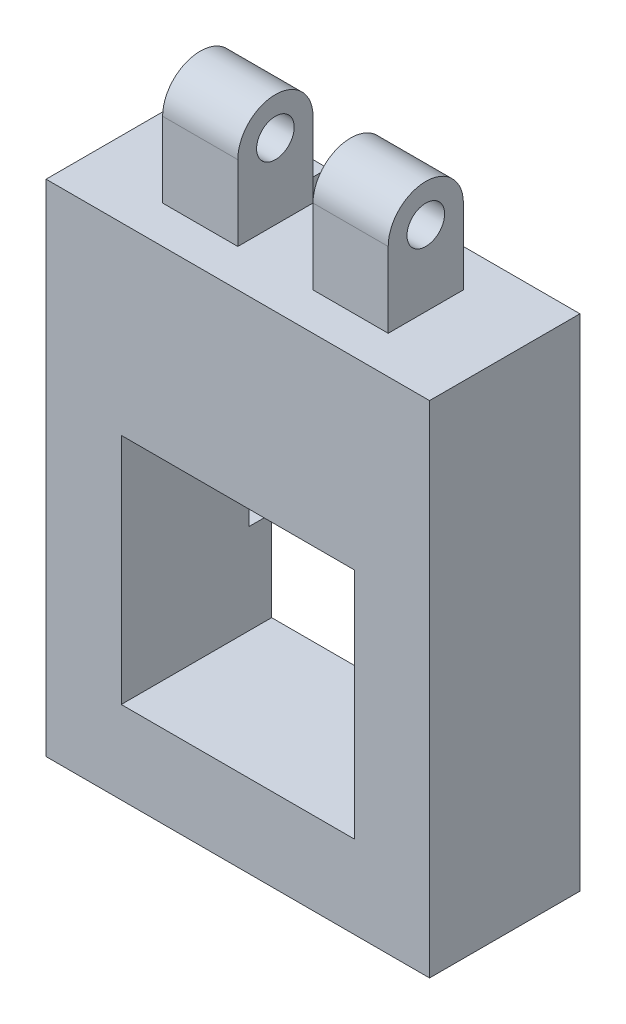
SolidWorks part; units mm, degrees
ref_plane "Front Plane" through (0, 0, 0) normal (0, 0, 1) x (1, 0, 0)
ref_plane "Top Plane" through (0, 0, 0) normal (0, 1, 0) x (1, 0, 0)
ref_plane "Right Plane" through (0, 0, 0) normal (1, 0, 0) x (0, 0, -1)
sketch "Sketch1" plane through (669.8418, 0, 0) normal (0, 0, 1) x (1, 0, 0)
  line L1 (-696.3103, 457.6379) -> (-646.3103, 457.6379)
  line L2 (-696.3103, 457.6379) -> (-696.3103, 417.6379)
  line L3 (-696.3103, 417.6379) -> (-646.3103, 417.6379)
  line L4 (-646.3103, 457.6379) -> (-646.3103, 417.6379)
  dimension "50" = 50
  dimension "D2" = 40
extrude "Boss-Extrude1" add sketch "Sketch1" along normal blind 10
sketch "Sketch5" plane through (23.5315, 0, 0) normal (1, 0, 0) x (0, 0, -1)
  line L0 (0, 417.6379) -> (0, 457.6379) construction
  line L1 (-8, 445.1379) -> (-2, 445.1379)
  line L2 (-8, 445.1379) -> (-8, 440.1379)
  line L3 (-8, 440.1379) -> (-2, 440.1379)
  line L4 (-2, 445.1379) -> (-2, 440.1379)
  line L5 (-8, 435.1379) -> (-2, 435.1379)
  line L6 (-8, 435.1379) -> (-8, 430.1379)
  line L7 (-8, 430.1379) -> (-2, 430.1379)
  line L8 (-2, 435.1379) -> (-2, 430.1379)
  line L9 (-10, 417.6379) -> (-10, 457.6379) construction
  line L10 (0, 437.6379) -> (-10, 437.6379)
  line L11 (-2, 440.1379) -> (-2, 437.6379)
  line L12 (-8, 435.1379) -> (-8, 437.6379)
  dimension "D1" = 5
  dimension "D2" = 2
  dimension "D3" = 2
  dimension "D4" = 2
  dimension "D5" = 2
  dimension "D6" = 5
  dimension "D7" = 5
extrude "Boss-Extrude3" add sketch "Sketch5" along normal blind 10 contours L4 L1 L2 L3 | L8 L5 L6 L7
sketch "Sketch6" plane through (669.8418, 445.1379, 0) normal (0, 1, 0) x (1, 0, 0)
  line L1 (-646.3103, -8) -> (-646.3103, -2) construction
  line L2 (-646.3103, -5) -> (-636.3103, -5) construction
  line L3 (-636.3103, -8) -> (-636.3103, -2) construction
  line L4 (-641.3103, -8) -> (-641.3103, -2) construction
  line L5 (-636.3103, -8) -> (-646.3103, -8) construction
  line L6 (-636.3103, -2) -> (-646.3103, -2) construction
  circle A1 centre (-641.3103, -5) radius 2
extrude "Cut-Extrude1" cut sketch "Sketch6" against normal blind 20
sketch "Sketch8" plane through (-26.4685, 0, 0) normal (-1, 0, 0) x (0, 0, 1)
  line L1 (0, 417.6379) -> (10, 417.6379)
  line L2 (0, 417.6379) -> (0, 457.6379)
  line L3 (0, 457.6379) -> (10, 457.6379)
  line L4 (10, 417.6379) -> (10, 457.6379)
extrude "Cut-Extrude2" cut sketch "Sketch8" against normal blind 25
sketch "Sketch9" plane through (0, 435.1379, 0) normal (0, 1, 0) x (1, 0, 0)
  line L1 (23.5315, -8) -> (33.5315, -8)
  line L2 (23.5315, -8) -> (23.5315, -2)
  line L3 (23.5315, -2) -> (33.5315, -2)
  line L4 (33.5315, -8) -> (33.5315, -2)
  circle A0 centre (28.5315, -5) radius 1.9309
extrude "Boss-Extrude4" add sketch "Sketch9" along normal blind 5
sketch "Sketch10" plane through (0, 0, 8) normal (0, 0, 1) x (1, 0, 0)
  line L0 (23.5315, 417.6379) -> (23.5315, 457.6379) construction
  line L1 (33.5315, 430.1379) -> (23.5315, 430.1379)
  line L2 (33.5315, 430.1379) -> (33.5315, 435.1379)
  line L3 (33.5315, 435.1379) -> (23.5315, 435.1379)
  line L4 (23.5315, 430.1379) -> (23.5315, 435.1379)
  line L6 (33.5315, 445.1379) -> (23.5315, 445.1379)
  line L7 (33.5315, 445.1379) -> (33.5315, 440.1379)
  line L8 (33.5315, 440.1379) -> (23.5315, 440.1379)
  line L9 (23.5315, 445.1379) -> (23.5315, 440.1379)
  dimension "D1" = 5
  dimension "D2" = 5
extrude "Cut-Extrude3" cut sketch "Sketch10" against normal blind 15 contours L7 L6 L9 L8 | L2 L1 L4 L3
mirror "Mirror1" about plane through (-1.4685, 0, 0) normal (1, 0, 0) of "Boss-Extrude1"
sketch "Sketch11" plane through (0, 457.6379, 0) normal (0, 1, 0) x (1, 0, 0)
  line L0 (23.5315, 0) -> (-26.4685, 0) construction
  line L1 (-3.9685, -2.5) -> (1.0315, -2.5)
  line L2 (-3.9685, -2.5) -> (-3.9685, -7.5)
  line L3 (-3.9685, -7.5) -> (1.0315, -7.5)
  line L4 (1.0315, -2.5) -> (1.0315, -7.5)
  line L5 (23.5315, -10) -> (-26.4685, -10) construction
  line L6 (23.5315, -10) -> (23.5315, 0) construction
  line L7 (-26.4685, -10) -> (-26.4685, 0) construction
  dimension "D1" = 2.5
  dimension "D2" = 2.5
  dimension "D3" = 22.5
  dimension "D4" = 22.5
extrude "Boss-Extrude5" add sketch "Sketch11" along normal blind 10
sketch "Sketch12" plane through (1.0315, 0, 0) normal (1, 0, 0) x (0, 0, -1)
  line L0 (-5, 467.6379) -> (-5, 457.6379) construction
  line L1 (-7.5, 467.6379) -> (-2.5, 467.6379) construction
  line L2 (-7.5, 457.6379) -> (-2.5, 457.6379) construction
  line L3 (-2.5, 462.6379) -> (-7.5, 462.6379) construction
  line L4 (-2.5, 467.6379) -> (-2.5, 457.6379) construction
  line L5 (-7.5, 467.6379) -> (-7.5, 457.6379) construction
  circle A1 centre (-5, 462.6379) radius 1.5
  dimension "D1" = 3
extrude "Cut-Extrude4" cut sketch "Sketch12" against normal blind 10
sketch "Sketch13" plane through (33.5315, 0, 0) normal (1, 0, 0) x (0, 0, -1)
  line L1 (-8, 435.1379) -> (-2, 435.1379)
  line L2 (-8, 435.1379) -> (-8, 440.1379)
  line L3 (-8, 440.1379) -> (-2, 440.1379)
  line L4 (-2, 435.1379) -> (-2, 440.1379)
extrude "Cut-Extrude5" cut sketch "Sketch13" against normal blind 10
sketch "Sketch15" plane through (0, 457.6379, 0) normal (0, 1, 0) x (1, 0, 0)
  line L1 (-8.9685, -7.5) -> (-3.9685, -7.5)
  line L2 (-8.9685, -7.5) -> (-8.9685, -2.5)
  line L3 (-8.9685, -2.5) -> (-3.9685, -2.5)
  line L4 (-3.9685, -7.5) -> (-3.9685, -2.5)
  line L5 (6.0315, -7.5) -> (1.0315, -7.5)
  line L6 (6.0315, -7.5) -> (6.0315, -2.5)
  line L7 (6.0315, -2.5) -> (1.0315, -2.5)
  line L8 (1.0315, -7.5) -> (1.0315, -2.5)
  dimension "D1" = 5
  dimension "D2" = 5
  dimension "D3" = 5
  dimension "D4" = 5
sketch "Sketch18" plane through (0, 467.6379, 0) normal (0, 1, 0) x (1, 0, 0)
  line L1 (-3.9685, -2.5) -> (1.0315, -2.5)
  line L2 (-3.9685, -2.5) -> (-3.9685, -7.5)
  line L3 (-3.9685, -7.5) -> (1.0315, -7.5)
  line L4 (1.0315, -2.5) -> (1.0315, -7.5)
extrude "Boss-Extrude7" add sketch "Sketch15" along normal blind 10
extrude "Cut-Extrude7" cut sketch "Sketch18" against normal blind 10
sketch "Sketch19" plane through (-8.9685, 0, 0) normal (-1, 0, 0) x (0, 0, 1)
  line L0 (5, 467.6379) -> (5, 457.6379) construction
  line L1 (7.5, 467.6379) -> (2.5, 467.6379) construction
  line L2 (10, 457.6379) -> (0, 457.6379) construction
  line L3 (7.5, 462.6379) -> (2.5, 462.6379) construction
  line L4 (7.5, 467.6379) -> (7.5, 457.6379) construction
  line L5 (2.5, 467.6379) -> (2.5, 457.6379) construction
  circle A0 centre (5, 462.6379) radius 1.25
  dimension "D1" = 2.5
extrude "Cut-Extrude8" cut sketch "Sketch19" against normal blind 43
sketch "Sketch20" plane through (6.0315, 0, 0) normal (1, 0, 0) x (0, 0, -1)
  line L0 (-7.5, 462.6379) -> (-7.5, 467.6379)
  line L1 (-7.5, 467.6379) -> (-2.5, 467.6379)
  line L2 (-2.5, 467.6379) -> (-2.5, 462.6379)
  circle A0 centre (-5, 462.6379) radius 2.5
  line M3 (-2.5, 457.6379) -> (-2.5, 467.6379)
  line M4 (-2.5, 467.6379) -> (-7.5, 467.6379)
  line M5 (-7.5, 467.6379) -> (-7.5, 457.6379)
extrude "Cut-Extrude9" cut sketch "Sketch20" against normal blind 20 contours A0 M3 M4 M5
sketch "Sketch21" plane through (0, 0, 10) normal (0, 0, 1) x (1, 0, 0)
  line L0 (23.5315, 457.6379) -> (-26.4685, 457.6379) construction
  line L1 (-9.2185, 445.3879) -> (6.2815, 445.3879)
  line L2 (-9.2185, 445.3879) -> (-9.2185, 429.8879)
  line L3 (-9.2185, 429.8879) -> (6.2815, 429.8879)
  line L4 (6.2815, 445.3879) -> (6.2815, 429.8879)
  line L5 (23.5315, 417.6379) -> (23.5315, 457.6379) construction
  point P4 (-1.4685, 457.6379)
  point P7 (-1.4685, 445.3879)
  point P10 (23.5315, 437.6379)
  point P11 (6.2815, 437.6379)
  dimension "D1" = 15.5
  dimension "D2" = 15.5
extrude "Cut-Extrude10" cut sketch "Sketch21" against normal blind 30
sketch "Sketch22" plane through (0, 0, 0) normal (0, 0, -1) x (-1, 0, 0)
  line L0 (-2.5315, 445.3879) -> (-2.5315, 457.6379)
  line L1 (-2.5315, 445.3879) -> (5.4685, 445.3879)
  line L2 (-2.5315, 457.6379) -> (5.4685, 457.6379)
  line L3 (5.4685, 445.3879) -> (5.4685, 457.6379)
  line L4 (-2.5315, 445.3879) -> (5.4685, 457.6379) construction
  line L5 (-2.5315, 457.6379) -> (5.4685, 445.3879) construction
  line L6 (-23.5315, 457.6379) -> (26.4685, 457.6379) construction
  line L15 (-6.2815, 445.3879) -> (9.2185, 445.3879) construction
  point P1 (1.4685, 451.5129)
  point P8 (1.4685, 457.6379)
  line M11 (26.4685, 457.6379) -> (-23.5315, 457.6379)
  dimension "D1" = 8
extrude "Cut-Extrude11" cut sketch "Sketch22" against normal blind 2 contours L1 L3 L0 M11
scale "Scale2" scale about centroid uniform scaling yes scale factor 2
sketch "Sketch23" plane through (0, 0, -5.0443) normal (0, 0, -1) x (-1, 0, 0)
  line L0 (16.9685, 452.8986) -> (16.9685, 421.8986) construction
  line L1 (17.9685, 420.8986) -> (-15.0315, 420.8986)
  line L2 (17.9685, 420.8986) -> (17.9685, 453.8986)
  line L3 (17.9685, 453.8986) -> (-15.0315, 453.8986)
  line L4 (-15.0315, 420.8986) -> (-15.0315, 453.8986)
  line L5 (16.9685, 421.8986) -> (-14.0315, 421.8986) construction
  line L6 (-14.0315, 421.8986) -> (-14.0315, 452.8986) construction
  line L7 (-14.0315, 452.8986) -> (-6.5315, 452.8986) construction
  line L9 (26.9685, 496.7939) -> (-24.0315, 496.7939)
  line L10 (26.9685, 496.7939) -> (26.9685, 410.8986)
  line L11 (26.9685, 410.8986) -> (-24.0315, 410.8986)
  line L12 (-24.0315, 496.7939) -> (-24.0315, 410.8986)
  line L13 (85.9607, 371.1118) -> (-71.5304, 371.1118)
  line L14 (85.9607, 371.1118) -> (85.9607, 495.2874)
  line L15 (85.9607, 495.2874) -> (-71.5304, 495.2874)
  line L16 (-71.5304, 371.1118) -> (-71.5304, 495.2874)
  dimension "D1" = 1
  dimension "D2" = 1
  dimension "D3" = 1
  dimension "D4" = 1
  dimension "D5" = 10
  dimension "D6" = 10
  dimension "D7" = 10
extrude "Cut-Extrude12" cut sketch "Sketch23" against normal blind 30
sketch "Sketch24" plane through (0, 0, -5.0443) normal (0, 0, -1) x (-1, 0, 0)
  line L0 (-14.0315, 421.8986) -> (-14.0315, 452.8986) construction
  line L1 (23.4685, 433.8986) -> (-20.5315, 433.8986)
  line L2 (23.4685, 433.8986) -> (23.4685, 440.8986)
  line L3 (23.4685, 440.8986) -> (-20.5315, 440.8986)
  line L4 (-20.5315, 433.8986) -> (-20.5315, 440.8986)
  line L5 (26.9685, 410.8986) -> (-24.0315, 410.8986) construction
  point P4 (1.4685, 433.8986)
  point P7 (1.4685, 410.8986)
  point P8 (-20.5315, 437.3986)
  point P11 (-14.0315, 437.3986)
  dimension "D1" = 7
  dimension "D2" = 44
extrude "Cut-Extrude13" cut sketch "Sketch24" against normal blind 3
